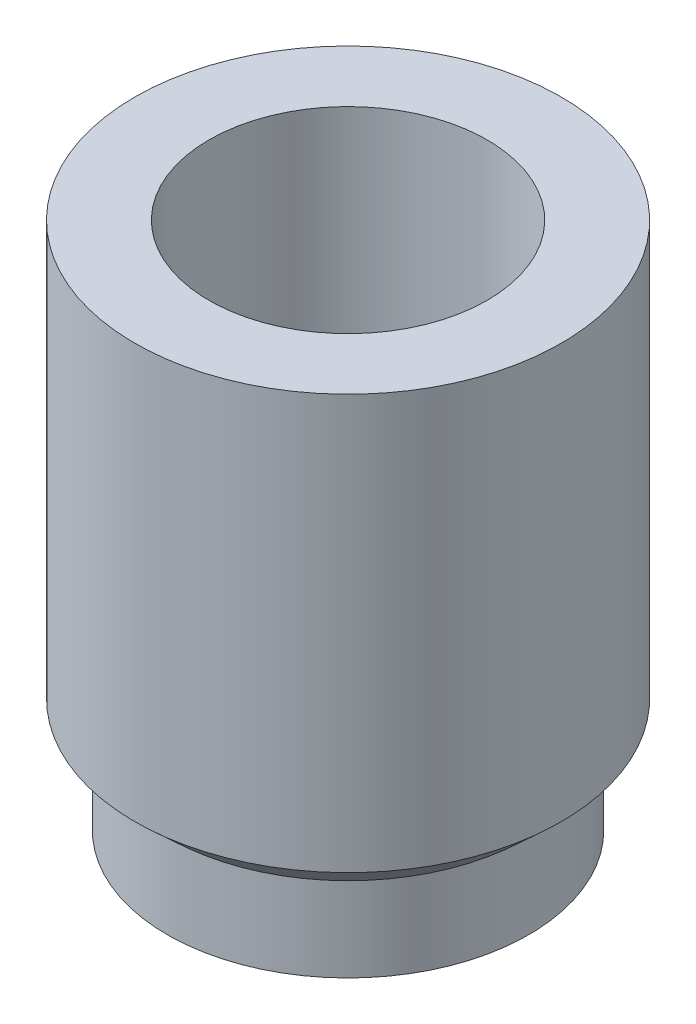
SolidWorks part; units mm, degrees
material "Brass"
ref_plane "Płaszczyzna przednia" through (0, 0, 0) normal (0, 0, 1) x (1, 0, 0)
ref_plane "Płaszczyzna górna" through (0, 0, 0) normal (0, 1, 0) x (1, 0, 0)
ref_plane "Płaszczyzna prawa" through (0, 0, 0) normal (1, 0, 0) x (0, 0, -1)
sketch "Sketch1" plane through (0, 0, 0) normal (0, 0, 1) x (1, 0, 0)
  line L0 (0, 0) -> (1.95, 0)
  line L1 (1.95, 0) -> (1.95, 0.9083)
  line L2 (1.95, 0.9083) -> (2.3, 1.2313)
  line L3 (2.3, 1.2313) -> (2.3, 5.7)
  line L4 (2.3, 5.7) -> (0, 5.7)
  line L5 (0, 5.7) -> (0, 0)
  dimension "D1" = 2.3
  dimension "D2" = 1.95
  dimension "D3" = 5.7
revolve "Revolve1" add sketch "Sketch1" angle 360 about L5
sketch "Sketch2" plane through (0, 5.7, 0) normal (0, 1, 0) x (1, 0, 0)
  circle A0 centre (0, 0) radius 1.5
  dimension "D1" = 3
extrude "Cut-Extrude1" cut sketch "Sketch2" against normal through all and the other way through all
